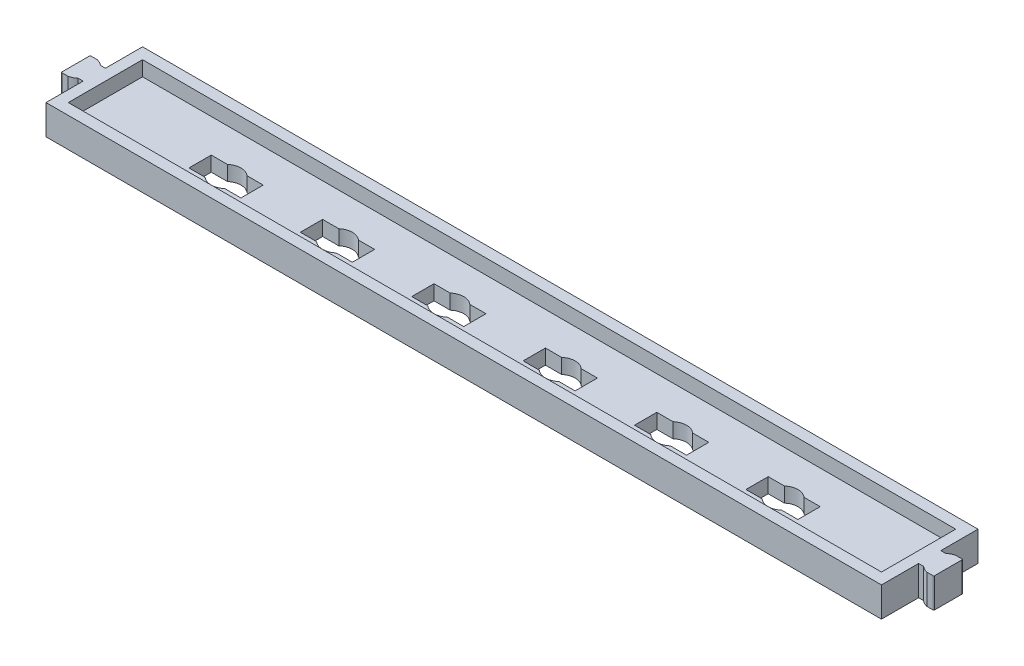
SolidWorks part; units mm, degrees
ref_plane "前视基准面" through (0, 0, 0) normal (0, 0, 1) x (1, 0, 0)
ref_plane "上视基准面" through (0, 0, 0) normal (0, 1, 0) x (1, 0, 0)
ref_plane "右视基准面" through (0, 0, 0) normal (1, 0, 0) x (0, 0, -1)
sketch "草图1" plane through (0, 0, 0) normal (0, 1, 0) x (1, 0, 0)
  line L0 (56.25, 6.5) -> (56.25, -6.5)
  line L1 (56.25, 6.5) -> (-56.25, 6.5)
  line L2 (56.25, -6.5) -> (-56.25, -6.5)
  line L3 (-56.25, 6.5) -> (-56.25, -6.5)
  line L4 (56.25, 6.5) -> (-56.25, -6.5) construction
  line L5 (56.25, -6.5) -> (-56.25, 6.5) construction
  point P1 (0, 0)
  dimension "D1" = 112.5
  dimension "D2" = 13
extrude "凸台-拉伸1" add sketch "草图1" along normal blind 4
sketch "草图2" plane through (0, 0, 0) normal (0, -1, 0) x (1, 0, 0)
  line L0 (56.25, 0) -> (58.25, 0) construction
  line L1 (56.25, 6.5) -> (56.25, -6.5) construction
  line L2 (58.25, 0) -> (58.75, 0) construction
  line L3 (56.25, -1.5) -> (56.25, 1.5)
  line L4 (56.25, 1.5) -> (56.9271, 1.5)
  line L5 (58.75, -1.95) -> (58.75, 1.95)
  line L6 (58.75, 1.95) -> (57.8056, 1.95)
  line L7 (58.75, -1.95) -> (57.8056, -1.95)
  line L8 (56.25, -1.5) -> (56.9271, -1.5)
  arc A0 (57.8056, 1.95) -> (56.9271, 1.5) centre (58.25, 0) ccw
  arc A1 (57.8056, -1.95) -> (56.9271, -1.5) centre (58.25, 0) cw
  dimension "D5" = 2
  dimension "D1" = 2
  dimension "D2" = 0.5
  dimension "D3" = 1.5
  dimension "D4" = 1.95
extrude "凸台-拉伸2" add sketch "草图2" against normal blind 4
mirror "镜向1" about plane through (0, 0, 0) normal (1, 0, 0) of "凸台-拉伸2"
sketch "草图3" plane through (0, 4, 0) normal (0, 1, 0) x (1, 0, 0)
  line L0 (54.75, 5) -> (54.75, -5)
  line L1 (54.75, 5) -> (-54.75, 5)
  line L2 (54.75, -5) -> (-54.75, -5)
  line L3 (-54.75, 5) -> (-54.75, -5)
  line L4 (54.75, 5) -> (-54.75, -5) construction
  line L5 (54.75, -5) -> (-54.75, 5) construction
  point P1 (0, 0)
  dimension "D1" = 10
  dimension "D2" = 109.5
extrude "切除-拉伸1" cut sketch "草图3" against normal blind 2
sketch "草图4" plane through (0, 2, 0) normal (0, 1, 0) x (1, 0, 0)
  line L0 (0, 0) -> (0, -1) construction
  line L1 (0, -1) -> (-7.5, -1) construction
  line L2 (-4, -2.5) -> (-4, 0.5)
  line L3 (-4, -2.5) -> (-6.1771, -2.5)
  line L4 (-4, 0.5) -> (-6.1771, 0.5)
  line L5 (-11, -2.5) -> (-11, 0.5)
  line L6 (-4, -2.5) -> (-11, 0.5) construction
  line L7 (-4, 0.5) -> (-11, -2.5) construction
  line L8 (-8.8229, 0.5) -> (-11, 0.5)
  line L9 (-8.8229, -2.5) -> (-11, -2.5)
  arc A0 (-8.8229, -2.5) -> (-6.1771, -2.5) centre (-7.5, -1) ccw
  arc A1 (-6.1771, 0.5) -> (-8.8229, 0.5) centre (-7.5, -1) ccw
  dimension "D3" = 4
  dimension "D1" = 1
  dimension "D2" = 7.5
  dimension "D4" = 3
  dimension "D5" = 7
extrude "切除-拉伸2" cut sketch "草图4" against normal up to next
pattern_linear "阵列(线性)1" count 4 spacing 15 along (1, 0, 0) count 3 spacing 15 along (-1, 0, 0) of "切除-拉伸2"
fillet "圆角1" radius 0.1 4 edges at (-58.75, 2, 1.95) (-58.75, 2, -1.95) (58.75, 2, 1.95) (58.75, 2, -1.95)
